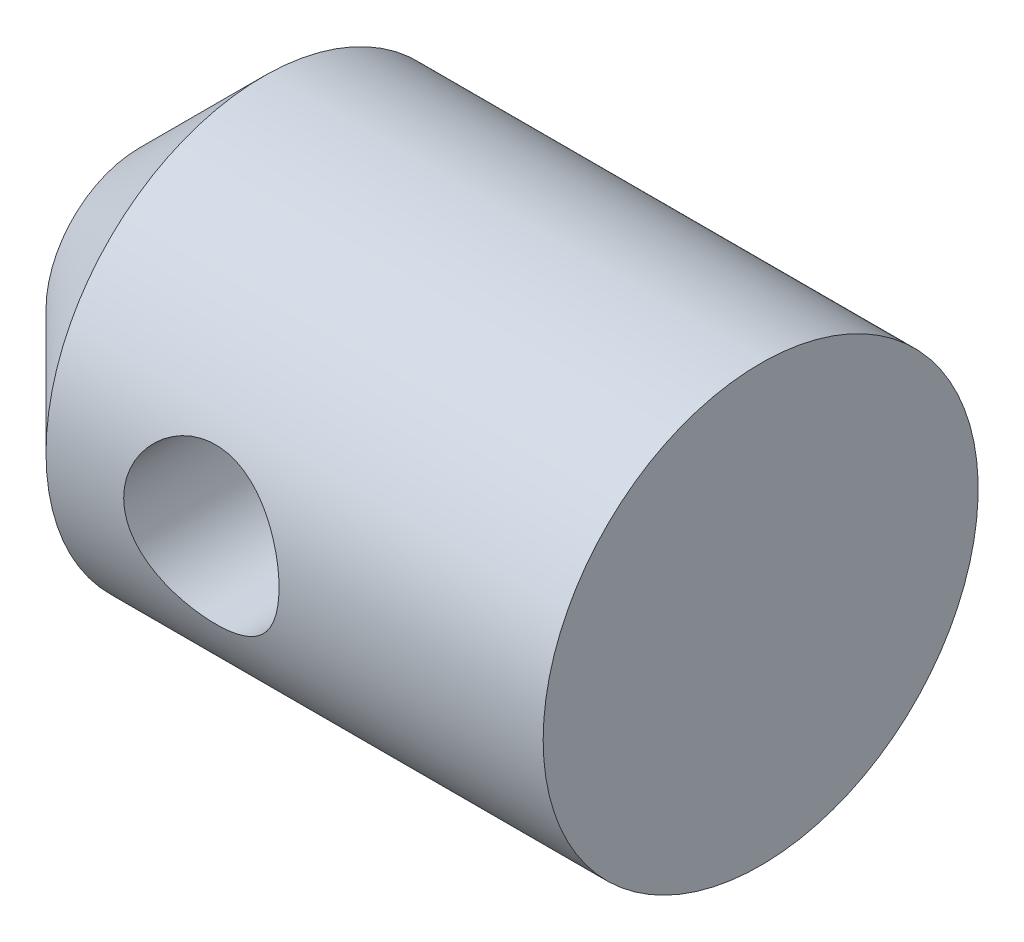
SolidWorks part; units mm, degrees
ref_plane "Front Plane" through (0, 0, 0) normal (0, 0, 1) x (1, 0, 0)
ref_plane "Top Plane" through (0, 0, 0) normal (0, 1, 0) x (1, 0, 0)
ref_plane "Right Plane" through (0, 0, 0) normal (1, 0, 0) x (0, 0, -1)
sketch "Sketch1" plane through (0, 0, 0) normal (0, 0, 1) x (1, 0, 0)
  line L0 (0, 3) -> (0, 0)
  line L1 (0, 0) -> (20, 0)
  line L2 (20, 0) -> (20, 7)
  line L3 (20, 7) -> (4, 7)
  line L4 (4, 7) -> (0, 3)
  dimension "D1" = 20
  dimension "D2" = 7
  dimension "D3" = 3
  dimension "D4" = 45
revolve "Revolve1" add sketch "Sketch1" angle 360 about L1
sketch "Sketch2" plane through (0, 0, 0) normal (-1, 0, 0) x (0, 0, 1)
  circle A0 centre (0, 0) radius 1
  circle A2 centre (0, 0) radius 3 construction
  dimension "D1" = 2
extrude "Cut-Extrude1" cut sketch "Sketch2" against normal blind 15
ref_plane "Plane1" through (0, 0, 7) normal (0, 0, 1) x (1, 0, 0)
sketch "Sketch3" plane through (0, 0, 7) normal (0, 0, 1) x (1, 0, 0)
  line L0 (4, 7) -> (4, -7) construction
  circle A0 centre (9, 0) radius 2.5
  dimension "D1" = 5
  dimension "D2" = 5
extrude "Cut-Extrude2" cut sketch "Sketch3" against normal through all both and the other way through all
